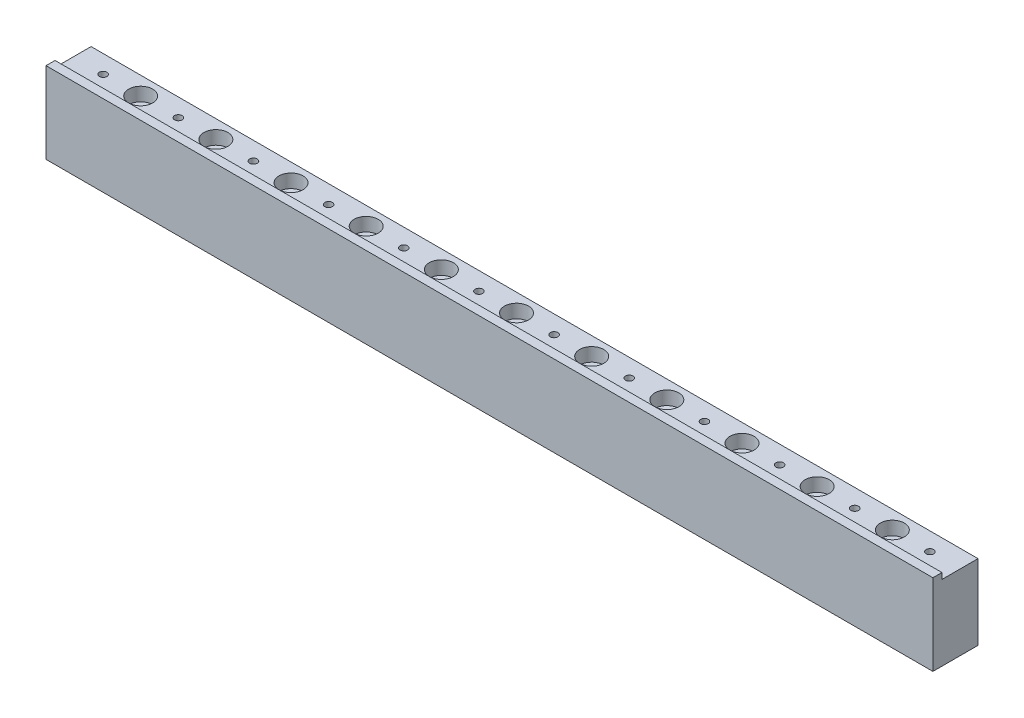
SolidWorks part; units mm, degrees
ref_plane "前视" through (0, 0, 0) normal (0, 0, 1) x (1, 0, 0)
ref_plane "上视" through (0, 0, 0) normal (0, 1, 0) x (1, 0, 0)
ref_plane "右视" through (0, 0, 0) normal (1, 0, 0) x (0, 0, -1)
sketch "草图2" plane through (0, 0, 0) normal (0, 1, 0) x (1, 0, 0)
  line L1 (0, 6) -> (295, 6)
  line L2 (0, 6) -> (0, -9)
  line L3 (0, -9) -> (295, -9)
  line L4 (295, 6) -> (295, -9)
  dimension "D1" = 15
  dimension "D2" = 6
  dimension "D3" = 295
extrude "拉伸1" add sketch "草图2" along normal blind 27
sketch "草图3" plane through (0, 27, 0) normal (0, 1, 0) x (1, 0, 0)
  point P0 (10, 0)
  dimension "D1" = 10
hole_wizard "M3 螺纹孔1" positions "3D草图1" profile "草图4" tap size "M3" standard "ISO"
sketch3d "3D草图1"
  point P0 (10, 27, 0)
sketch "草图4" plane through (10, 27, 0) normal (1, 0, 0) x (0, 0, 1)
  line L0 (0, 0) -> (0, 8.2511)
  line L1 (0, 8.2511) -> (1.25, 7.5)
  line L2 (1.25, 7.5) -> (1.25, 0)
  line L5 (1.25, 0) -> (0, 0)
  line L10 (0, 8.2511) -> (-1.25, 7.5) construction
  line L11 (0, -6.35) -> (0, 107.95) construction
  dimension "螺纹孔钻头直径" = 2.5
  dimension "螺纹孔钻头深度" = 7.5
  dimension "导头角度" = 118
cosmetic thread "孔螺蚊线1" parameters "D1"=6, "D2"=3
pattern_linear "阵列(线性)1" count 12 spacing 25 along (1, 0, 0) of "M3 螺纹孔1"
sketch "草图5" plane through (0, 0, 9) normal (0, 0, 1) x (1, 0, 0)
  line L0 (147.5, 0) -> (147.5, 27) construction
  line L1 (0, 0) -> (295, 0) construction
  line L2 (0, 27) -> (295, 27) construction
  point P6 (147.5, 13.5)
sketch "草图6" plane through (295, 0, 0) normal (1, 0, 0) x (0, 0, -1)
  line L0 (-9, 27) -> (6, 27) construction
  line L1 (-6, 27) -> (6, 27)
  line L2 (-6, 27) -> (-6, 25)
  line L3 (-6, 25) -> (6, 25)
  line L4 (6, 27) -> (6, 25)
  line L5 (6, 27) -> (6, 0) construction
  line L7 (-9, 27) -> (-9, 0) construction
  dimension "D1" = 3
  dimension "D2" = 2
extrude "切除-拉伸1" cut sketch "草图6" against normal up to next
hole_wizard "M4 六角凹头螺钉的柱形沉头孔1" positions "草图8" profile "草图7" counterbore size "M4" standard "ISO" end condition through all
sketch "草图8" plane through (0, 25, 0) normal (0, 1, 0) x (-1, 0, 0)
  line L0 (-8.75, 0) -> (-19.0982, 0) construction
  line L2 (0, -6) -> (0, 6) construction
  circle A0 centre (-10, 0) radius 1.25 construction
  circle A1 centre (-10, 0) radius 1.25 construction
  point P0 (-22.5, 0)
  dimension "D1" = 22.5
sketch "草图7" plane through (22.5, 25, 0) normal (1, 0, 0) x (0, 0, 1)
  line L0 (0, 0) -> (0, 25)
  line L1 (0, 25) -> (2.25, 25)
  line L3 (2.25, 25) -> (2.25, 4.5)
  line L4 (2.25, 4.5) -> (4, 4.5)
  line L5 (4, 4.5) -> (4, 0)
  line L7 (4, 0) -> (0, 0)
  line L11 (0, -6.35) -> (0, 107.95) construction
  dimension "通孔孔直径" = 4.5
  dimension "通孔孔深度" = 25
  dimension "柱形沉头孔直径" = 8
  dimension "柱形沉头孔深度" = 4.5
pattern_linear "阵列(线性)2" count 11 spacing 25 along (1, 0, 0) of "M4 六角凹头螺钉的柱形沉头孔1"
sketch "草图9" plane through (0, 0, 0) normal (0, -1, 0) x (1, 0, 0)
  line L0 (22.5, 0) -> (0, 0) construction
  line L1 (274.75, 0) -> (295, 0) construction
  line L2 (295, 9) -> (295, -6) construction
  circle A0 centre (272.5, 0) radius 2.25 construction
hole_wizard "Ø5.0 (5) 直径孔1" positions "草图11" profile "草图10" hole size "Ø5.0" standard "GB"
sketch "草图11" plane through (0, 0, 0) normal (0, -1, 0) x (-1, 0, 0)
  line L0 (-22.5, 0) -> (0, 0) construction
  line L1 (-274.75, 0) -> (-295, 0) construction
  point P0 (-11.25, 0)
  point P4 (-284.875, 0)
sketch "草图10" plane through (11.25, 0, 0) normal (1, 0, 0) x (0, 0, -1)
  line L0 (0, 0) -> (0, 8)
  line L1 (0, 8) -> (2.5, 8)
  line L2 (2.5, 8) -> (2.5, 0)
  line L5 (2.5, 0) -> (0, 0)
  line L10 (0, 8) -> (-2.5, 8) construction
  line L11 (0, -6.35) -> (0, 107.95) construction
  dimension "孔直径" = 5
  dimension "孔深度" = 8
  dimension "导头角度" = 180
